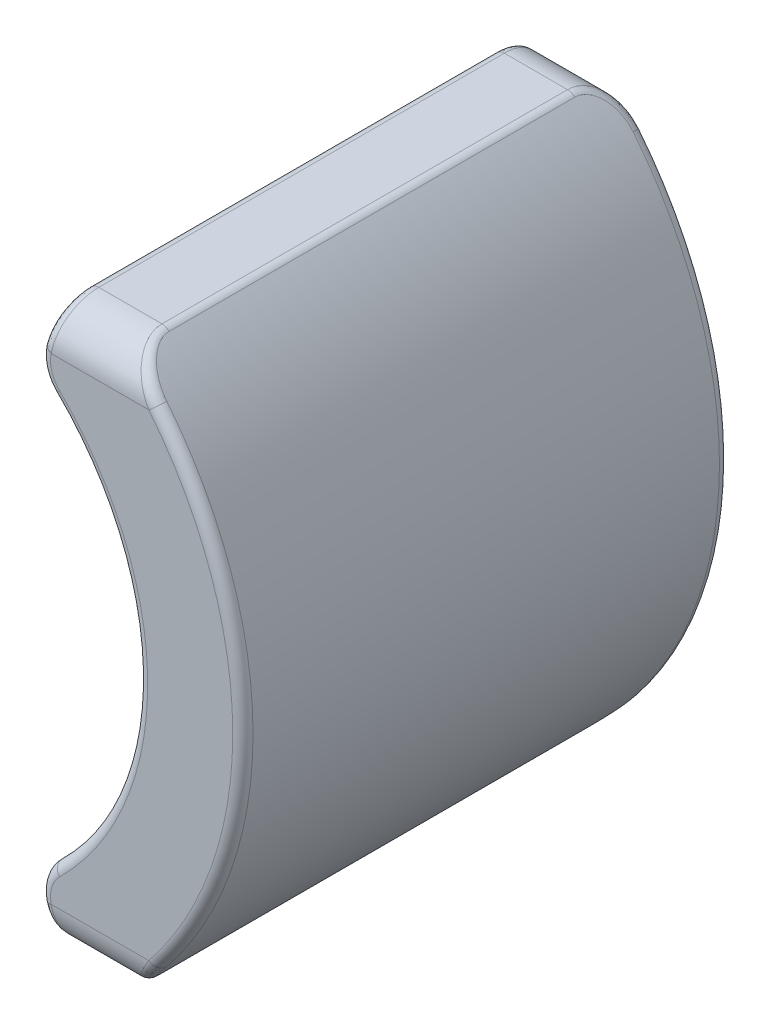
SolidWorks part; units mm, degrees
ref_plane "Front Plane" through (0, 0, 0) normal (0, 0, 1) x (1, 0, 0)
ref_plane "Top Plane" through (0, 0, 0) normal (0, 1, 0) x (1, 0, 0)
ref_plane "Right Plane" through (0, 0, 0) normal (1, 0, 0) x (0, 0, -1)
sketch "Sketch1" plane through (0, 0, 0) normal (0, 0, 1) x (1, 0, 0)
  line L0 (0, 0) -> (9.63, 0) construction
  line L1 (6.7381, -6.88) -> (4.8781, -6.88)
  line L2 (4.8781, -6.88) -> (4.5318, -5.38)
  line L3 (4.8781, 6.88) -> (4.5318, 5.38)
  line L4 (6.7381, 6.88) -> (4.8781, 6.88)
  arc A0 (6.7381, 6.88) -> (6.7381, -6.88) centre (0, 0) cw
  arc A1 (4.5318, 5.38) -> (4.5318, -5.38) centre (0, 0) cw
  dimension "D1" = 9.63
  dimension "D2" = 6.88
  dimension "D3" = 1.86
  dimension "D4" = 103
  dimension "D5" = 1.5
extrude "Boss-Extrude1" add sketch "Sketch1" along normal blind 12
fillet "Fillet1" radius 1 2 edges at (4.5318, -5.38, 6) (4.5318, 5.38, 6)
fillet "Fillet2" radius 1 4 edges at (5.8081, -6.88, 0) (5.8081, -6.88, 12) (5.8081, 6.88, 12) (5.8081, 6.88, 0)
fillet "Fillet3" radius 0.25 24 edges at (4.8161, -6.6112, 0.3178) (4.8781, -6.88, 6) (4.8161, -6.6112, 11.6822) (4.6879, -5.4113, 12) (7.0343, 0, 12) (4.6879, 5.4113, 12) (4.8161, 6.6112, 11.6822) (4.8781, 6.88, 6) (4.8161, 6.6112, 0.3178) (6.8685, -6.7498, 0.5066) (6.7381, -6.88, 6) (6.9882, -6.6258, 11.6661) (9.63, 0, 12) (6.8685, 6.7498, 11.4934) (6.7381, 6.88, 6) (6.9882, 6.6258, 0.3339) (4.6879, 5.4113, 0) (7.0343, 0, 0) (4.6879, -5.4113, 0) (9.63, 0, 0)
